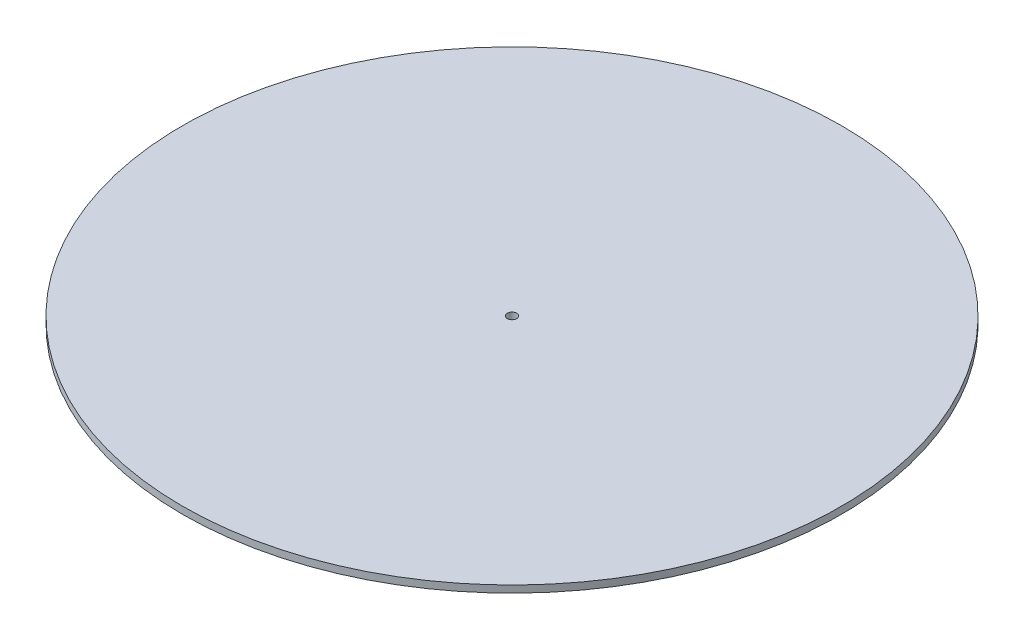
SolidWorks part; units mm, degrees
ref_plane "Front Plane" through (0, 0, 0) normal (0, 0, 1) x (1, 0, 0)
ref_plane "Top Plane" through (0, 0, 0) normal (0, 1, 0) x (1, 0, 0)
ref_plane "Right Plane" through (0, 0, 0) normal (1, 0, 0) x (0, 0, -1)
sketch "Sketch1" plane through (0, 0, 0) normal (0, 1, 0) x (1, 0, 0)
  circle A0 centre (0, 0) radius 140
  circle A1 centre (0, 0) radius 2
  dimension "D1" = 280
  dimension "D2" = 4
extrude "Boss-Extrude1" add sketch "Sketch1" along normal blind 3
